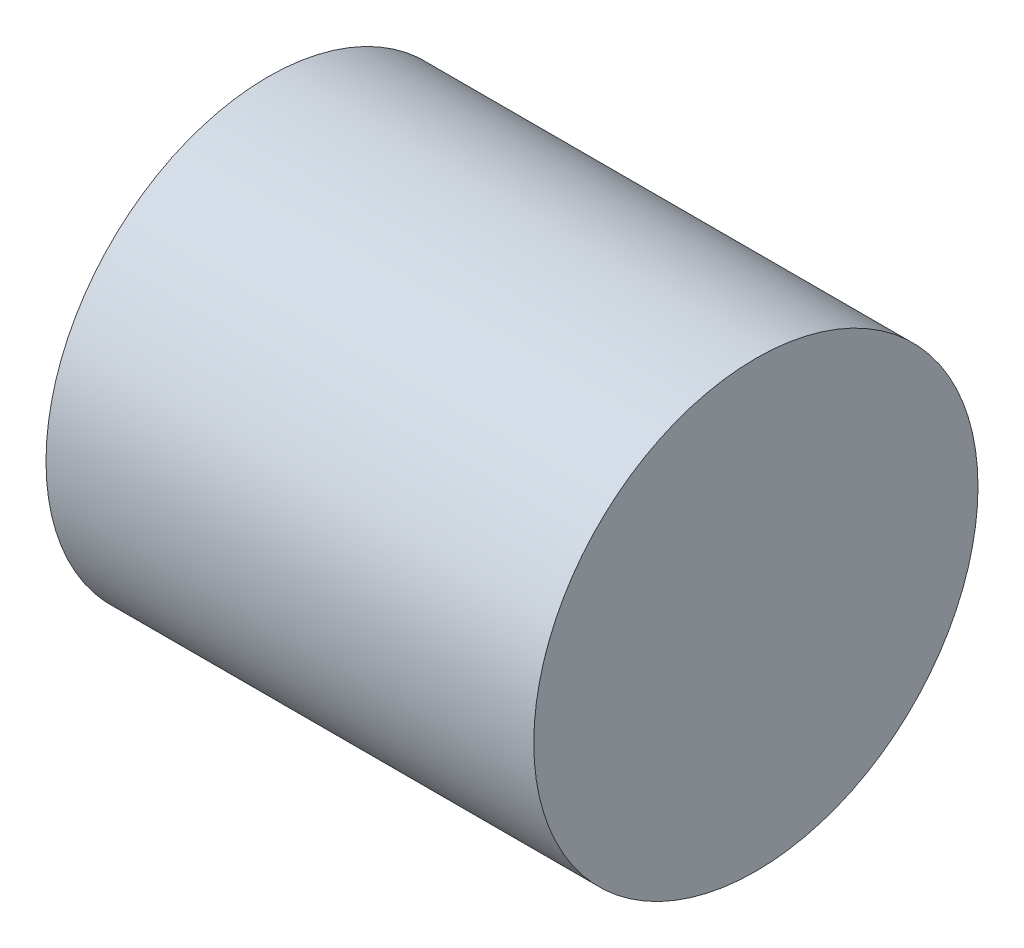
SolidWorks part; units mm, degrees
ref_plane "Front Plane" through (0, 0, 0) normal (0, 0, 1) x (1, 0, 0)
ref_plane "Top Plane" through (0, 0, 0) normal (0, 1, 0) x (1, 0, 0)
ref_plane "Right Plane" through (0, 0, 0) normal (1, 0, 0) x (0, 0, -1)
sketch "Sketch1" plane through (0, 0, 0) normal (1, 0, 0) x (0, 0, -1)
  circle A0 centre (86.7984, 438.1663) radius 25.9391
  point P2 (64.3666, 451.1914)
extrude "Boss-Extrude1" add sketch "Sketch1" along normal blind 56.9646
